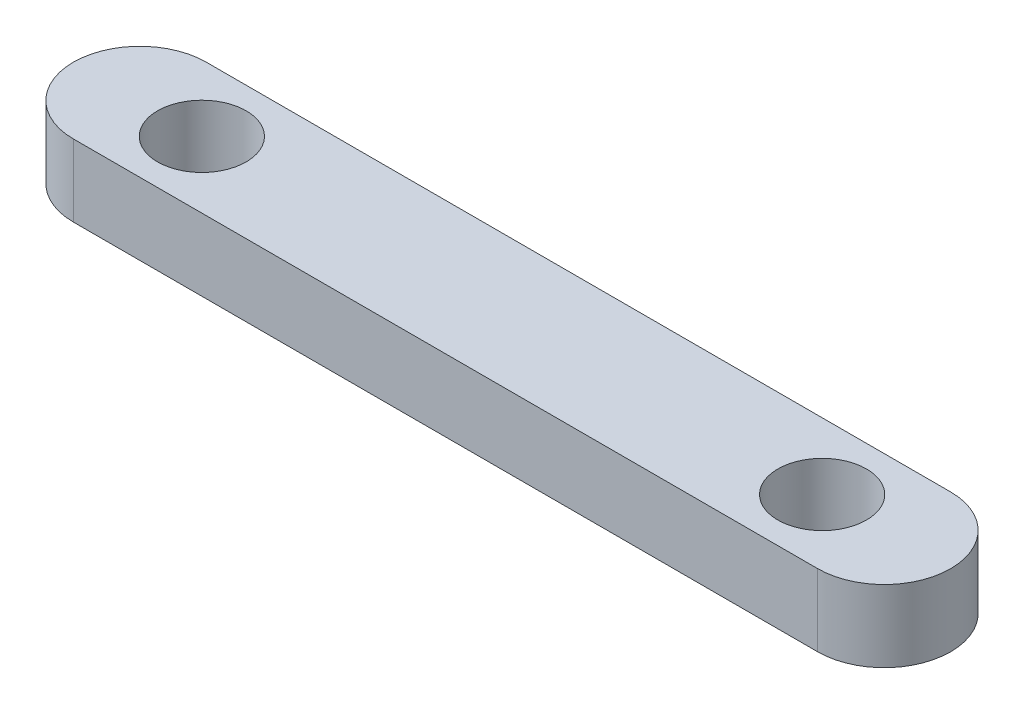
SolidWorks part; units mm, degrees
material "PLA"
ref_plane "Front Plane" through (0, 0, 0) normal (0, 0, 1) x (1, 0, 0)
ref_plane "Top Plane" through (0, 0, 0) normal (0, 1, 0) x (1, 0, 0)
ref_plane "Right Plane" through (0, 0, 0) normal (1, 0, 0) x (0, 0, -1)
sketch "Sketch1" plane through (0, 0, 0) normal (0, 1, 0) x (1, 0, 0)
  line L0 (0, 0) -> (21, 0) construction
  line L3 (0, 1.875) -> (21, 1.875)
  line L4 (0, -1.875) -> (21, -1.875)
  line L5 (0, 1.875) -> (1.75, 0) construction
  line L6 (10.5, 0) -> (10.5, 3.1248) construction
  arc A2 (0, 1.875) -> (0, -1.875) centre (0, 0) ccw
  arc A3 (21, -1.875) -> (21, 1.875) centre (21, 0) ccw
  circle A5 centre (1.75, 0) radius 1.25
  circle A6 centre (19.25, 0) radius 1.25
  point P3 (10.5, 0)
  dimension "D3" = 1.75
  dimension "D5" = 17.5
  dimension "D1" = 21
  dimension "D2" = 3.75
  dimension "D4" = 1.875
extrude "Boss-Extrude1" add sketch "Sketch1" along normal blind 2.032
sketch "Sketch2" plane through (0, 2.032, 0) normal (0, 1, 0) x (1, 0, 0)
  line L0 (10.5, -1.875) -> (10.5, 4.09) construction
  circle A2 centre (0, 0) radius 1.25 construction
  circle A3 centre (21, 0) radius 1.25 construction
